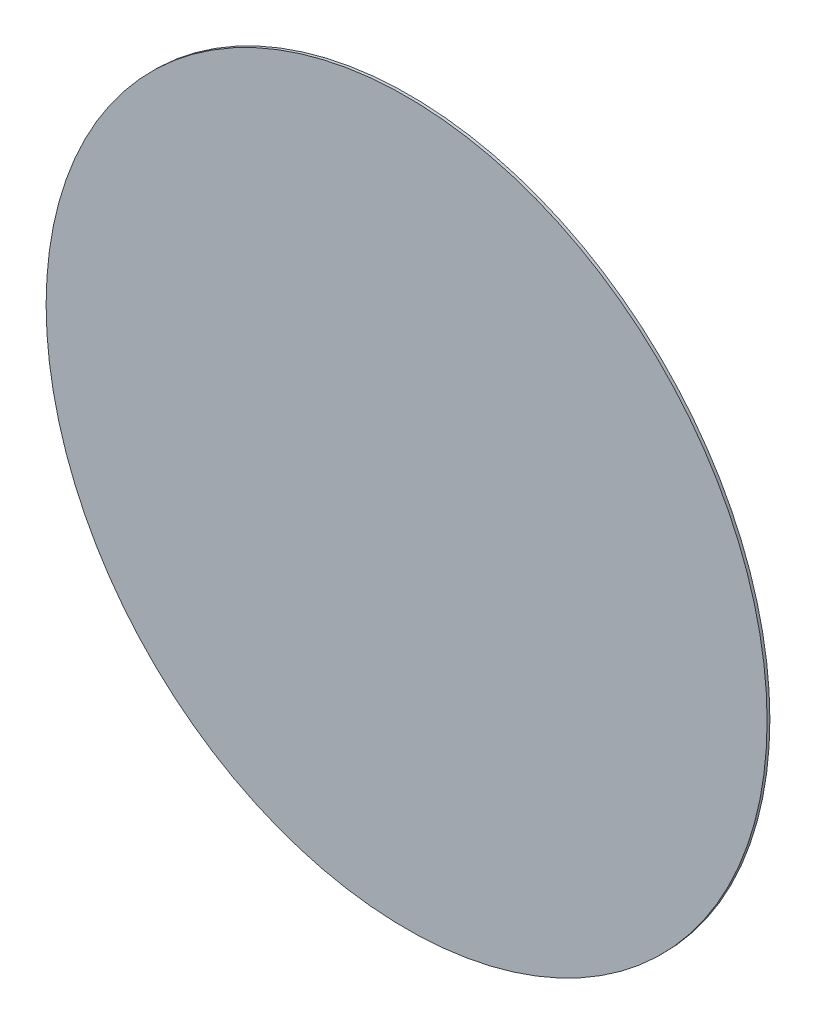
SolidWorks part; units mm, degrees
ref_plane "Front Plane" through (0, 0, 0) normal (0, 0, 1) x (1, 0, 0)
ref_plane "Top Plane" through (0, 0, 0) normal (0, 1, 0) x (1, 0, 0)
ref_plane "Right Plane" through (0, 0, 0) normal (1, 0, 0) x (0, 0, -1)
sketch "Sketch1" plane through (0, 0, 0) normal (0, 0, 1) x (1, 0, 0)
  circle A0 centre (0, 0) radius 13
  circle A1 centre (0, 0) radius 1 construction
  dimension "D1" = 26
  dimension "D2" = 2
extrude "Extrude1" add sketch "Sketch1" along normal blind 0.1
